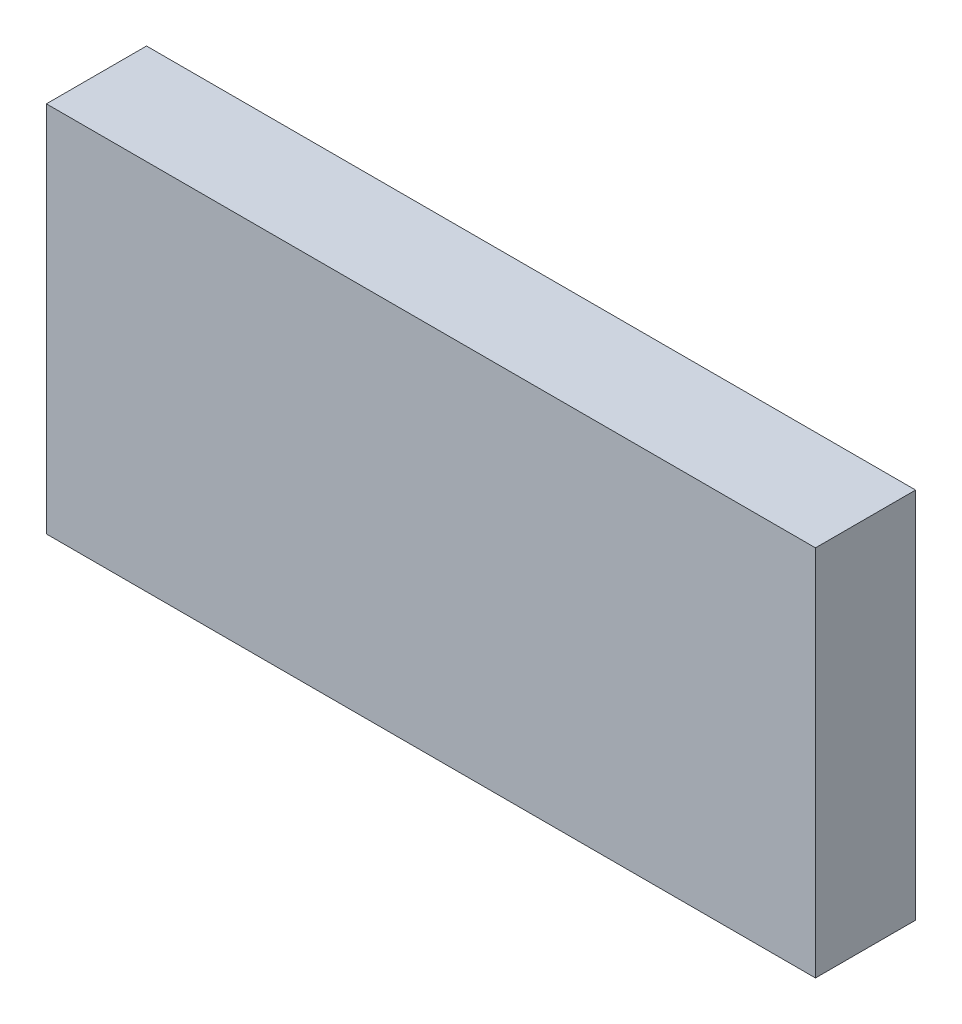
SolidWorks part; units mm, degrees
ref_plane "Front Plane" through (0, 0, 0) normal (0, 0, 1) x (1, 0, 0)
ref_plane "Top Plane" through (0, 0, 0) normal (0, 1, 0) x (1, 0, 0)
ref_plane "Right Plane" through (0, 0, 0) normal (1, 0, 0) x (0, 0, -1)
sketch "Sketch1" plane through (0, 0, 0) normal (0, 0, 1) x (1, 0, 0)
  line L1 (-28.1748, 19.6711) -> (20.5932, 19.6711)
  line L2 (-28.1748, 19.6711) -> (-28.1748, -3.9509)
  line L3 (-28.1748, -3.9509) -> (20.5932, -3.9509)
  line L4 (20.5932, 19.6711) -> (20.5932, -3.9509)
  dimension "D1" = 48.768
  dimension "D2" = 23.622
extrude "Boss-Extrude1" add sketch "Sketch1" along normal blind 6.35
